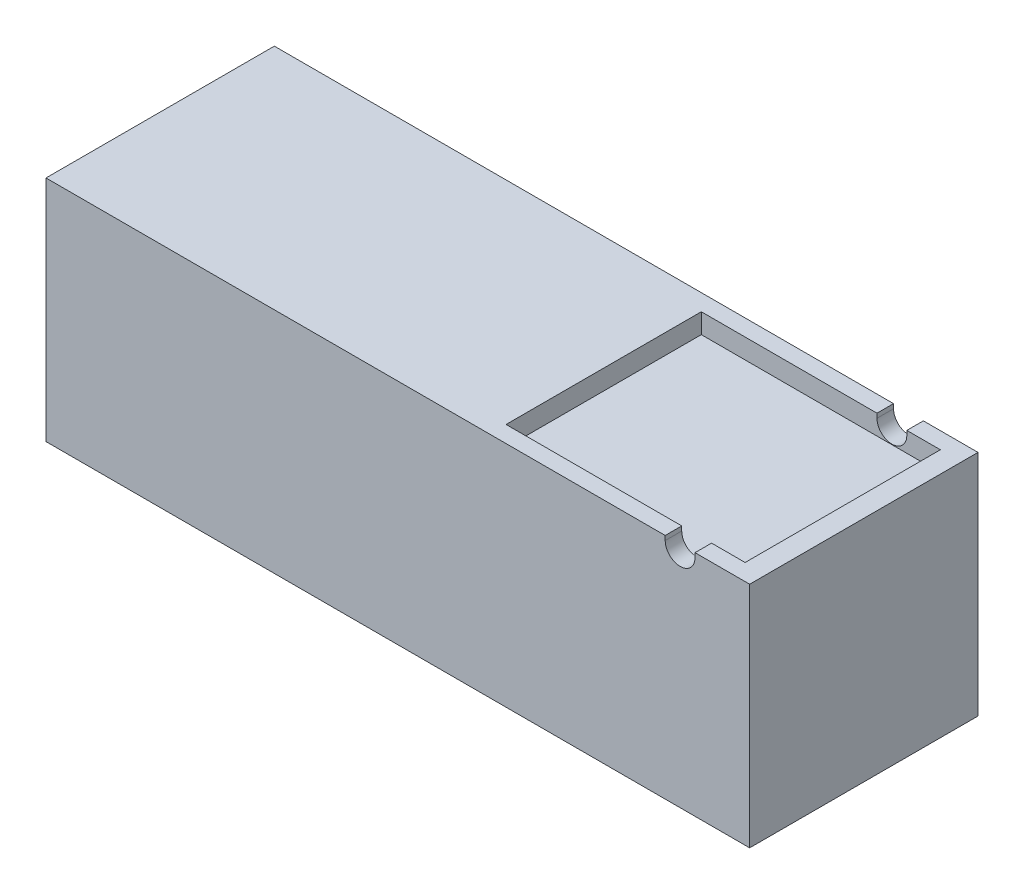
SolidWorks part; units mm, degrees
ref_plane "Front Plane" through (0, 0, 0) normal (0, 0, 1) x (1, 0, 0)
ref_plane "Top Plane" through (0, 0, 0) normal (0, 1, 0) x (1, 0, 0)
ref_plane "Right Plane" through (0, 0, 0) normal (1, 0, 0) x (0, 0, -1)
sketch "Sketch1" plane through (0, 0, 0) normal (0, 1, 0) x (1, 0, 0)
  line L1 (-75.5, 24.5) -> (75.5, 24.5)
  line L2 (-75.5, 24.5) -> (-75.5, -24.5)
  line L3 (-75.5, -24.5) -> (75.5, -24.5)
  line L4 (75.5, 24.5) -> (75.5, -24.5)
  line L5 (-75.5, 24.5) -> (75.5, -24.5) construction
  line L6 (-75.5, -24.5) -> (75.5, 24.5) construction
  point P0 (0, 0)
  dimension "D1" = 151
  dimension "D2" = 49
extrude "Boss-Extrude1" add sketch "Sketch1" along normal blind 49
sketch "Sketch2" plane through (0, 49, 0) normal (0, 1, 0) x (1, 0, 0)
  line L0 (45.3244, -20.7) -> (45.3244, -20.95) construction
  line L1 (19.6744, 20.95) -> (70.9744, 20.95)
  line L2 (19.6744, 20.95) -> (19.6744, -20.95)
  line L3 (19.6744, -20.95) -> (70.9744, -20.95)
  line L4 (70.9744, 20.95) -> (70.9744, -20.95)
  line L5 (70.7244, -20.7) -> (19.9244, -20.7) construction
  line L6 (19.9244, 0) -> (19.6744, 0) construction
  line L7 (19.9244, -20.7) -> (19.9244, 20.7) construction
  line L8 (45.3244, 20.7) -> (45.3244, 20.95) construction
  line L9 (19.9244, 20.7) -> (70.7244, 20.7) construction
  line L10 (70.7244, 0) -> (70.9744, 0) construction
  line L11 (70.7244, 20.7) -> (70.7244, -20.7) construction
  dimension "D1" = 0.25
extrude "Cut-Extrude1" cut sketch "Sketch2" against normal blind 4.2596
sketch "Sketch5" plane through (0, 49, 0) normal (0, 1, 0) x (1, 0, 0)
  line L0 (70.9744, 20.95) -> (70.9744, 27.2187) construction
sketch "Sketch6" plane through (0, 0, -24.5) normal (0, 0, -1) x (-1, 0, 0)
  line L0 (-71.024, 49) -> (-63.774, 49) construction
  line L1 (-75.5, 49) -> (75.5, 49) construction
  line L2 (-60.574, 48.05) -> (-60.574, 49) construction
  line L3 (-63.774, 48.05) -> (-63.774, 49)
  line L4 (-57.374, 48.05) -> (-57.374, 49)
  arc A0 (-63.774, 48.05) -> (-57.374, 48.05) centre (-60.574, 48.05) ccw
  arc A1 (-57.374, 49) -> (-63.774, 49) centre (-60.574, 49) ccw
  point P6 (-60.574, 48.525)
  point P11 (0, 0)
  point P12 (0, 0)
  point P13 (-60.574, 49.5686)
  point P14 (0, 0)
  point P15 (-60.574, 43.7136)
  point P17 (0, 0)
  point P18 (0, 0)
  dimension "D2" = 3.2
  dimension "D1" = 7.25
  dimension "D3" = 0.95
extrude "Cut-Extrude2" cut sketch "Sketch6" against normal through all and the other way through all
